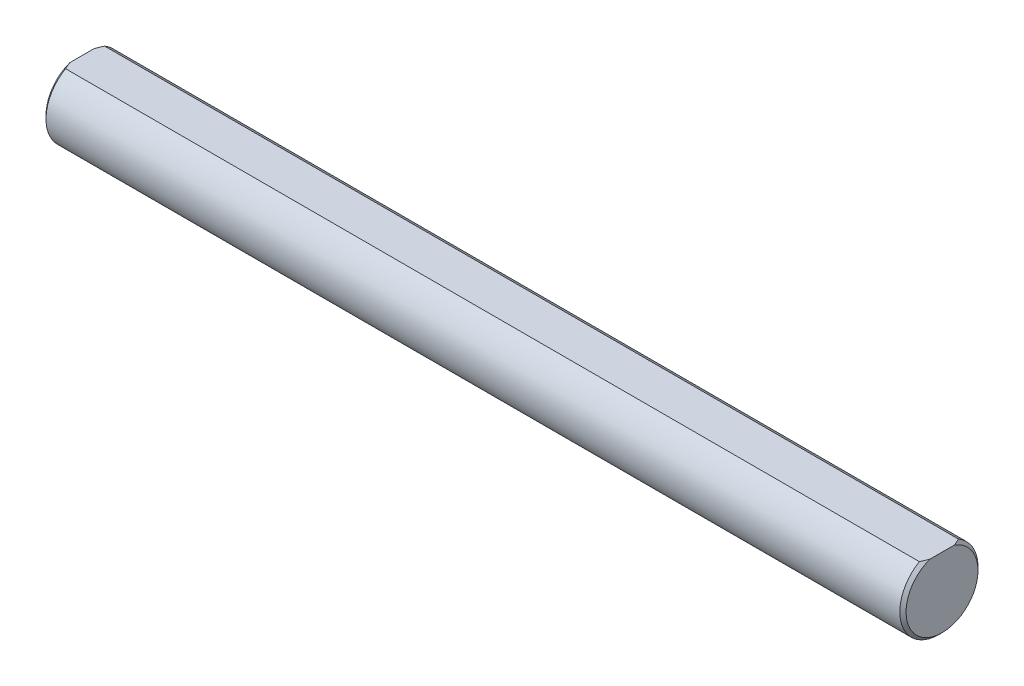
SolidWorks part; units mm, degrees
material "AISI 1045 Steel, cold drawn"
ref_plane "Front Plane" through (0, 0, 0) normal (0, 0, 1) x (1, 0, 0)
ref_plane "Top Plane" through (0, 0, 0) normal (0, 1, 0) x (1, 0, 0)
ref_plane "Right Plane" through (0, 0, 0) normal (1, 0, 0) x (0, 0, -1)
sketch "Sketch1" plane through (0, 0, 0) normal (1, 0, 0) x (0, 0, -1)
  circle A2 centre (0, 0) radius 3.175
  dimension "D1" = 6.35
extrude "Boss-Extrude1" add sketch "Sketch1" along normal blind 69.85
chamfer "Chamfer1" distance 0.254 angle 45 2 edges at (69.85, 0, -3.175) (0, 0, -3.175)
sketch "Sketch2" plane through (69.85, 0, 0) normal (1, 0, 0) x (0, 0, -1)
  line L0 (-1.5875, 2.7496) -> (1.5875, 2.7496)
  circle A0 centre (0, 0) radius 3.175 construction
  arc A1 (1.5875, 2.7496) -> (-1.5875, 2.7496) centre (0, 0) ccw
  dimension "D1" = 3.175
extrude "Cut-Extrude2" cut sketch "Sketch2" against normal through all
